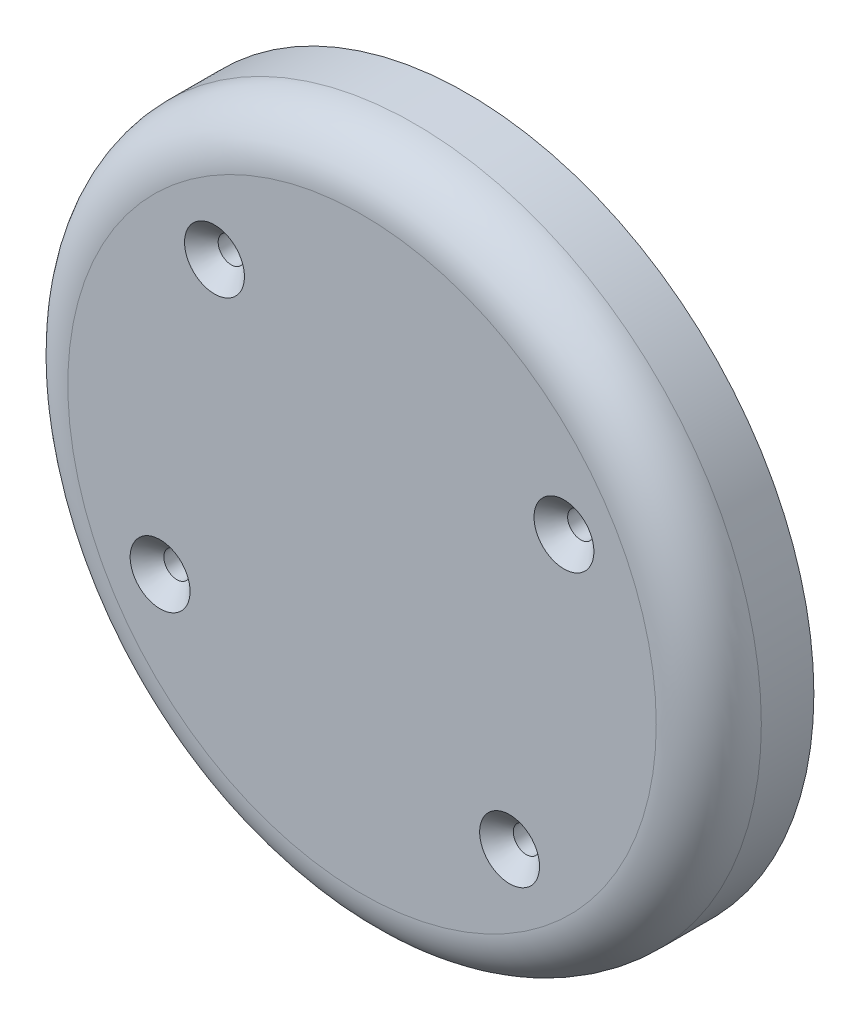
SolidWorks part; units mm, degrees
ref_plane "Alzado" through (0, 0, 0) normal (0, 0, 1) x (1, 0, 0)
ref_plane "Planta" through (0, 0, 0) normal (0, 1, 0) x (1, 0, 0)
ref_plane "Vista lateral" through (0, 0, 0) normal (1, 0, 0) x (0, 0, -1)
sketch "Croquis1" plane through (0, 0, 0) normal (0, 0, 1) x (1, 0, 0)
  circle A0 centre (0, 0) radius 33
  dimension "D1" = 66
extrude "Saliente-Extruir1" add sketch "Croquis1" along normal blind 10
shell "Vaciado1" thickness 3
fillet "Redondeo1" radius 5 2 edges at (30, 0, 7) (33, 0, 10)
sketch "Croquis2" plane through (0, 0, 10) normal (0, 0, 1) x (1, 0, 0)
  circle A0 centre (14.0418, -17.2826) radius 1.25 construction
  circle A1 centre (19.2159, 11.2521) radius 1.25 construction
  circle A2 centre (-19.2159, -11.2521) radius 1.25 construction
  circle A3 centre (-14.0418, 17.2826) radius 1.25 construction
  circle A4 centre (14.0418, -17.2826) radius 1.25
  circle A5 centre (19.2159, 11.2521) radius 1.25
  circle A6 centre (-19.2159, -11.2521) radius 1.25
  circle A7 centre (-14.0418, 17.2826) radius 1.25
extrude "Cortar-Extruir1" cut sketch "Croquis2" against normal up to next
chamfer "Chaflán1" distance 1.6 angle 45 4 edges at (15.2918, -17.2826, 10) (-17.9659, -11.2521, 10) (-12.7918, 17.2826, 10) (20.4659, 11.2521, 10)
